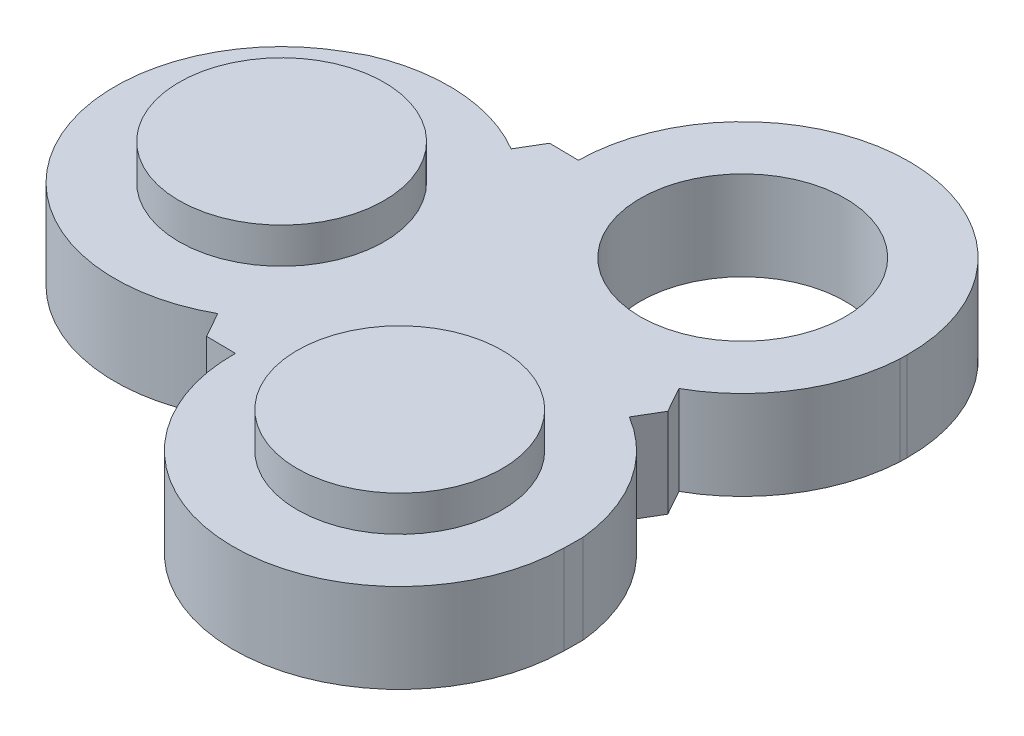
SolidWorks part; units mm, degrees
ref_plane "Front Plane" through (0, 0, 0) normal (0, 0, 1) x (1, 0, 0)
ref_plane "Top Plane" through (0, 0, 0) normal (0, 1, 0) x (1, 0, 0)
ref_plane "Right Plane" through (0, 0, 0) normal (1, 0, 0) x (0, 0, -1)
sketch "Sketch5" plane through (0, 0, 0) normal (0, 1, 0) x (1, 0, 0)
  circle A0 centre (0, 0) radius 30
  point P0 (0, 0)
  dimension "D1" = 60
extrude "Boss-Extrude1" add sketch "Sketch5" along normal blind 5
sketch "Sketch6" plane through (0, 5, 0) normal (0, 1, 0) x (1, 0, 0)
  circle A1 centre (5.5647, 9.4306) radius 5.75
  circle A2 centre (5.3253, -9.5678) radius 5.75
  circle A3 centre (-11.0082, 0.1387) radius 5.75
  dimension "D1" = 11.5
  dimension "D2" = 11.5
  dimension "D3" = 11.5
  dimension "D4" = 19
  dimension "D5" = 19
  dimension "D7" = 19
extrude "Cut-Extrude1" cut sketch "Sketch6" against normal blind 50
sketch "Sketch9" plane through (0, 5, 0) normal (0, 1, 0) x (1, 0, 0)
  line L0 (5.5647, 9.4306) -> (5.3253, -9.5678) construction
  line L1 (14.8992, 9.3131) -> (14.6599, -9.6854)
  line L3 (5.3253, -9.5678) -> (-11.0082, 0.1387) construction
  line L4 (0.5264, -17.6431) -> (-15.8071, -7.9366)
  line L6 (-11.0082, 0.1387) -> (5.5647, 9.4306) construction
  line L7 (-15.5778, 8.2888) -> (0.9951, 17.5808)
  arc A0 (14.8992, 9.3131) -> (-3.7699, 9.5482) centre (5.5647, 9.4306) ccw
  arc A1 (-4.0093, -9.4502) -> (14.6599, -9.6854) centre (5.3253, -9.5678) ccw
  arc A2 (0.5264, -17.6431) -> (10.1242, -1.4926) centre (5.3253, -9.5678) ccw
  arc A3 (-6.2093, 8.2139) -> (-15.8071, -7.9366) centre (-11.0082, 0.1387) ccw
  arc A4 (-15.5778, 8.2888) -> (-6.4386, -8.0115) centre (-11.0082, 0.1387) ccw
  arc A5 (10.1342, 1.2805) -> (0.9951, 17.5808) centre (5.5647, 9.4306) ccw
  point P4 (5.445, -0.0686)
  point P9 (-2.8414, -4.7146)
  point P17 (-2.7218, 4.7847)
extrude "Cut-Extrude-Thin1" cut sketch "Sketch9" against normal blind 50 thin thin type one direction wall 10
sketch "Sketch10" plane through (0, 5, 0) normal (0, 1, 0) x (1, 0, 0)
  circle A0 centre (5.3253, -9.5678) radius 5.75
  circle A1 centre (-11.0082, 0.1387) radius 5.75
  dimension "D1" = 11.5
  dimension "D2" = 11.5
extrude "Boss-Extrude2" add sketch "Sketch10" along normal blind 2 and the other way blind 2 separate body
